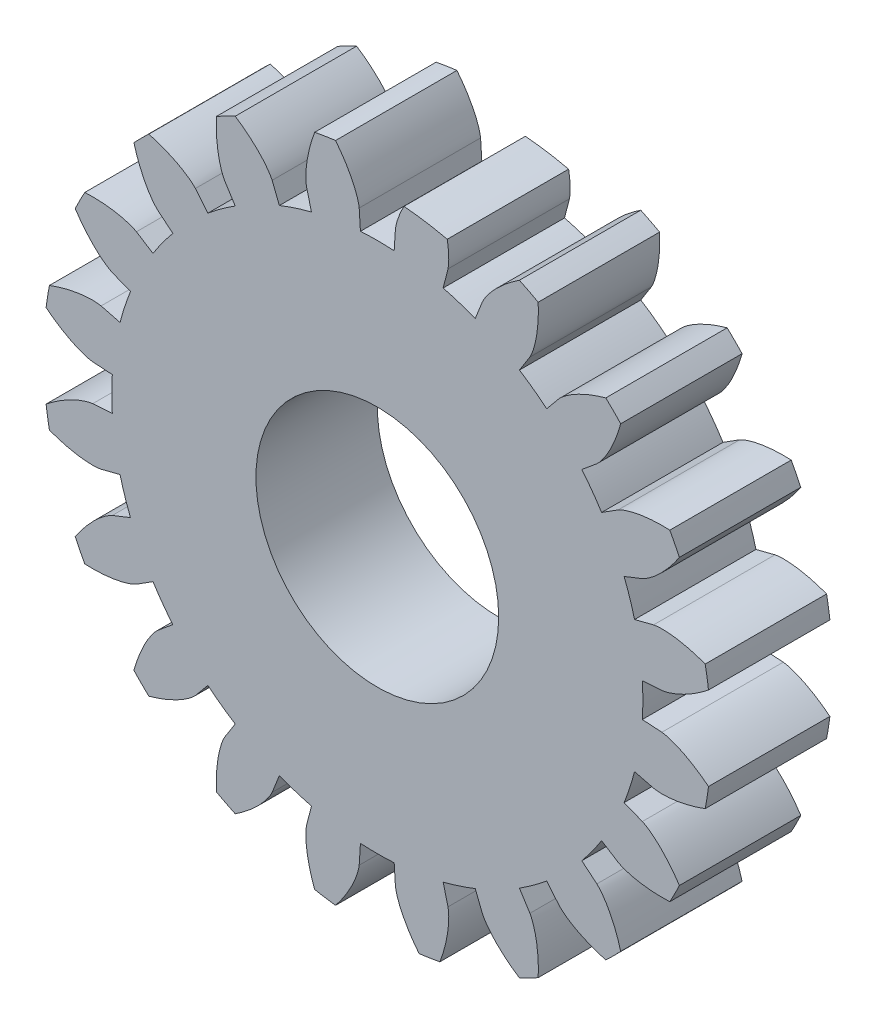
SolidWorks part; units mm, degrees
other "Markup1" [suppressed]
sketch "Sketch10" [suppressed] plane through (-27.2856, -27.2856, 5) normal (0, 0, 1) x (1, 0, 0)
ref_plane "Front Plane" through (0, 0, 0) normal (0, 0, 1) x (1, 0, 0)
ref_plane "Top Plane" through (0, 0, 0) normal (0, 1, 0) x (1, 0, 0)
ref_plane "Right Plane" through (0, 0, 0) normal (1, 0, 0) x (0, 0, -1)
sketch "Sketch1" plane through (0, 0, 0) normal (0, 0, 1) x (1, 0, 0)
  circle A0 centre (0, 0) radius 27.5
  dimension "GearOverall" = 55
extrude "Boss-Extrude1" add sketch "Sketch1" along normal mid plane 10
sketch "Sketch2" plane through (0, 0, 5) normal (0, 0, 1) x (1, 0, 0)
  line L0 (0, 0) -> (0, 27.5) construction
  line L1 (0, 0) -> (-27.5, 0) construction
  line L2 (-1.4922, 23.4426) -> (0, 0) construction
  line L3 (0, 0) -> (-3.9344, 23.1582) construction
  line L4 (-3.9344, 23.1582) -> (-1.5092, 23.5702) construction
  line L5 (0, 0) -> (-6.3336, 22.62) construction
  line L6 (-6.3336, 22.62) -> (-1.5958, 23.9466) construction
  line L7 (0, 0) -> (-8.6633, 21.8341) construction
  line L8 (-8.6633, 21.8341) -> (-1.8036, 24.5559) construction
  line L9 (0, 0) -> (-10.8981, 20.8089) construction
  line L10 (-10.8981, 20.8089) -> (-2.1812, 25.3742) construction
  line L11 (0, 0) -> (-13.0136, 19.5558) construction
  line L12 (-13.0136, 19.5558) -> (-2.7736, 26.37) construction
  line L13 (0, 0) -> (-14.9864, 18.0883) construction
  line L14 (-14.9864, 18.0883) -> (-3.6205, 27.5051) construction
  line L15 (0, 0) -> (-16.795, 16.4227) construction
  line L16 (-16.795, 16.4227) -> (-4.7559, 28.7348) construction
  circle A0 centre (0, 0) radius 27.5 construction
  circle A1 centre (0, 0) radius 23.49 construction
  circle A2 centre (0, 0) radius 25 construction
  arc A3 (0, 23.49) -> (-1.4922, 23.4426) centre (0, 0) ccw construction
  arc A4 (-1.4922, 23.4426) -> (1.4922, 23.4426) centre (0, 0) cw
  arc A5 (-4.7559, 28.7348) -> (4.7559, 28.7348) centre (0, 1.6492) cw
  spline S0 degree 3 poles (-1.4922, 23.4426) (-1.5097, 23.6135) (-1.5981, 23.9909) (-1.823, 24.6405) (-2.2058, 25.4584) (-3.0904, 26.9331) (-4.0211, 28.0142) (-4.7559, 28.7348) knots 0 0 0 0 0.081636 0.183677 0.326533 0.510206 1 1 1 1
  spline S1 degree 3 poles (1.4922, 23.4426) (1.5097, 23.6135) (1.5981, 23.9909) (1.823, 24.6405) (2.2058, 25.4584) (3.0904, 26.9331) (4.0211, 28.0142) (4.7559, 28.7348) knots 0 0 0 0 0.081636 0.183677 0.326533 0.510206 1 1 1 1
  point P14 (-1.96, 24.923)
  dimension "BaseCircle" = 46.98
  dimension "PCD" = 50
  dimension "MirrorDist" = 1.96
  dimension "D2" = 6
  dimension "InvoluteGAP" = 2.46
  dimension "D3" = 4.92
  dimension "D4" = 6
  dimension "D5" = 7.38
  dimension "D6" = 6
  dimension "D7" = 9.84
  dimension "D8" = 6
  dimension "D9" = 12.3
  dimension "D10" = 6
  dimension "D11" = 14.76
  dimension "D12" = 6
  dimension "D13" = 17.22
  dimension "D14" = 6
extrude "Cut-Extrude1" cut sketch "Sketch2" against normal through all contours A5 S1 A4 S0
sketch "Sketch4" plane through (0, 0, 5) normal (0, 0, 1) x (1, 0, 0)
  line L0 (0, 0) -> (-1.4922, 23.4426)
  line L1 (0, 0) -> (1.4922, 23.4426)
  arc A0 (1.4922, 23.4426) -> (-1.4922, 23.4426) centre (0, 0) ccw construction
  arc A1 (1.4922, 23.4426) -> (-1.4922, 23.4426) centre (0, 0) ccw
  circle A2 centre (0, 0) radius 21.875
  arc M1 (1.4922, 23.4426) -> (-1.4922, 23.4426) centre (0, 0) ccw
  dimension "Dedendum" = 43.75
extrude "Cut-Extrude2" cut sketch "Sketch4" against normal through all contours A2 L1 L0 M1
pattern_circular "CirPattern1" count 20 over 360 about axis through (0, 0, 5) along (0, 0, -1) of "Cut-Extrude1", "Cut-Extrude2"
sketch "Sketch5" plane through (0, 0, 5) normal (0, 0, 1) x (1, 0, 0)
  circle A0 centre (0, 0) radius 10
  dimension "ID" = 20
extrude "Cut-Extrude3" cut sketch "Sketch5" against normal through all
sketch "Sketch9" plane through (0, 0, 5) normal (0, 0, 1) x (1, 0, 0)
  line L0 (1.3896, 21.8308) -> (1.6199, 25.4485) construction
  line L1 (6.3234, 24.7035) -> (6.8194, 26.6411)
  line L2 (5.4245, 21.1918) -> (6.3234, 24.7035) construction
  line L3 (1.6199, 25.4485) -> (1.7469, 27.4445)
  line L4 (6.3234, 24.7035) -> (6.8194, 26.6411)
  line L5 (6.3234, 24.7035) -> (6.8234, 24.5755)
  line L6 (6.8194, 26.6411) -> (7.3194, 26.5131)
  line L7 (6.8234, 24.5755) -> (7.3194, 26.5131)
  line L8 (1.6199, 25.4485) -> (1.7469, 27.4445)
  line L9 (1.6199, 25.4485) -> (1.1199, 25.4803)
  line L10 (1.7469, 27.4445) -> (1.2469, 27.4763)
  line L11 (1.1199, 25.4803) -> (1.2469, 27.4763)
  arc A0 (6.8194, 26.6411) -> (1.7469, 27.4445) centre (0, 0) ccw
  arc A1 (6.3234, 24.7035) -> (1.6199, 25.4485) centre (0, 0) ccw
  circle A3 centre (0, 0) radius 27.5 construction
  circle A4 centre (0, 0) radius 25.5 construction
  point P1 (26.5, 0)
  point P13 (26.2984, 8.0402)
  dimension "D1" = 0.5
  dimension "ToothLossDist" = 2
  dimension "D2" = 0.5
extrude "Cut-Extrude5" cut sketch "Sketch9" against normal through all contours L11 L9 L3 L10 | L5 L7 L6 L1
equation "\"D3@Sketch2\" = \"InvoluteGAP@Sketch2\" * 2"
equation "\"D5@Sketch2\" = \"InvoluteGAP@Sketch2\" * 3"
equation "\"D7@Sketch2\" = \"InvoluteGAP@Sketch2\" * 4"
equation "\"D9@Sketch2\" = \"InvoluteGAP@Sketch2\" * 5"
equation "\"D11@Sketch2\" = \"InvoluteGAP@Sketch2\" * 6"
equation "\"D13@Sketch2\" = \"InvoluteGAP@Sketch2\" * 7"
